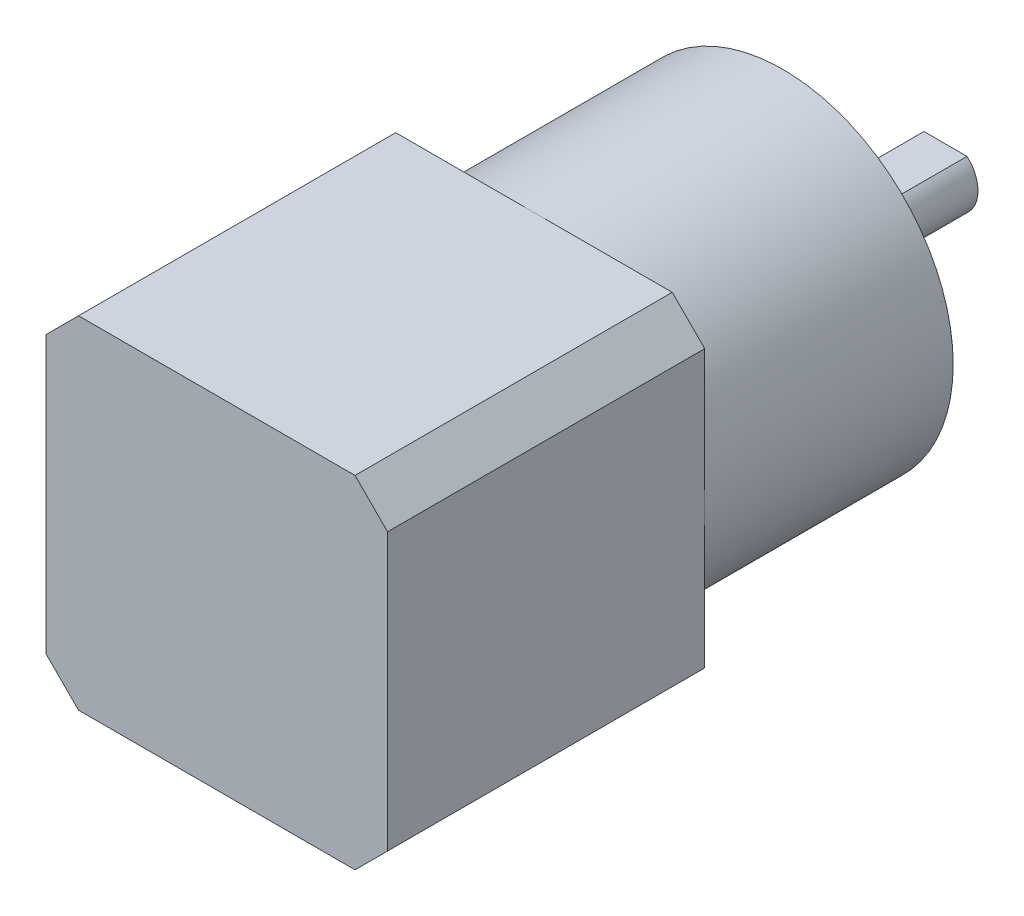
SolidWorks part; units mm, degrees
ref_plane "Front Plane" through (0, 0, 0) normal (0, 0, 1) x (1, 0, 0)
ref_plane "Top Plane" through (0, 0, 0) normal (0, 1, 0) x (1, 0, 0)
ref_plane "Right Plane" through (0, 0, 0) normal (1, 0, 0) x (0, 0, -1)
sketch "Sketch1" plane through (0, 0, 0) normal (0, 0, 1) x (1, 0, 0)
  line L1 (-21, 21) -> (21, 21)
  line L2 (-21, 21) -> (-21, -21)
  line L3 (-21, -21) -> (21, -21)
  line L4 (21, 21) -> (21, -21)
  line L5 (-21, 21) -> (21, -21) construction
  line L6 (-21, -21) -> (21, 21) construction
  point P0 (0, 0)
  dimension "D1" = 42
  dimension "D2" = 42
extrude "Boss-Extrude1" add sketch "Sketch1" along normal blind 39
chamfer "Chamfer1" distance 4 angle 45 4 edges at (-21, -21, 19.5) (21, -21, 19.5) (-21, 21, 19.5) (21, 21, 19.5)
sketch "Sketch2" plane through (0, 0, 0) normal (0, 0, -1) x (-1, 0, 0)
  circle A0 centre (0, 0) radius 20.95
  dimension "D1" = 41.9
extrude "Boss-Extrude2" add sketch "Sketch2" along normal blind 30.6
sketch "Sketch3" plane through (0, 0, -30.6) normal (0, 0, -1) x (-1, 0, 0)
  circle A0 centre (0, 0) radius 4
  dimension "D1" = 8
extrude "Boss-Extrude3" add sketch "Sketch3" along normal blind 20
sketch "Sketch4" plane through (0, 0, -50.6) normal (0, 0, -1) x (-1, 0, 0)
  line L1 (-2.6458, 3) -> (2.6458, 3)
  arc A2 (2.6458, 3) -> (-2.6458, 3) centre (0, 0) ccw
  dimension "D1" = 3
extrude "Cut-Extrude1" cut sketch "Sketch4" against normal blind 15
sketch "Sketch5" plane through (0, 0, -30.6) normal (0, 0, -1) x (-1, 0, 0)
  line L0 (0, 0) -> (12.0208, 12.0208) construction
  circle A0 centre (0, 0) radius 17 construction
  circle A1 centre (12.0208, 12.0208) radius 2
  circle A2 centre (12.0208, -12.0208) radius 2
  circle A3 centre (-12.0208, -12.0208) radius 2
  circle A4 centre (-12.0208, 12.0208) radius 2
  point P14 (0, 0)
  dimension "D1" = 4
extrude "Cut-Extrude2" cut sketch "Sketch5" against normal blind 20
